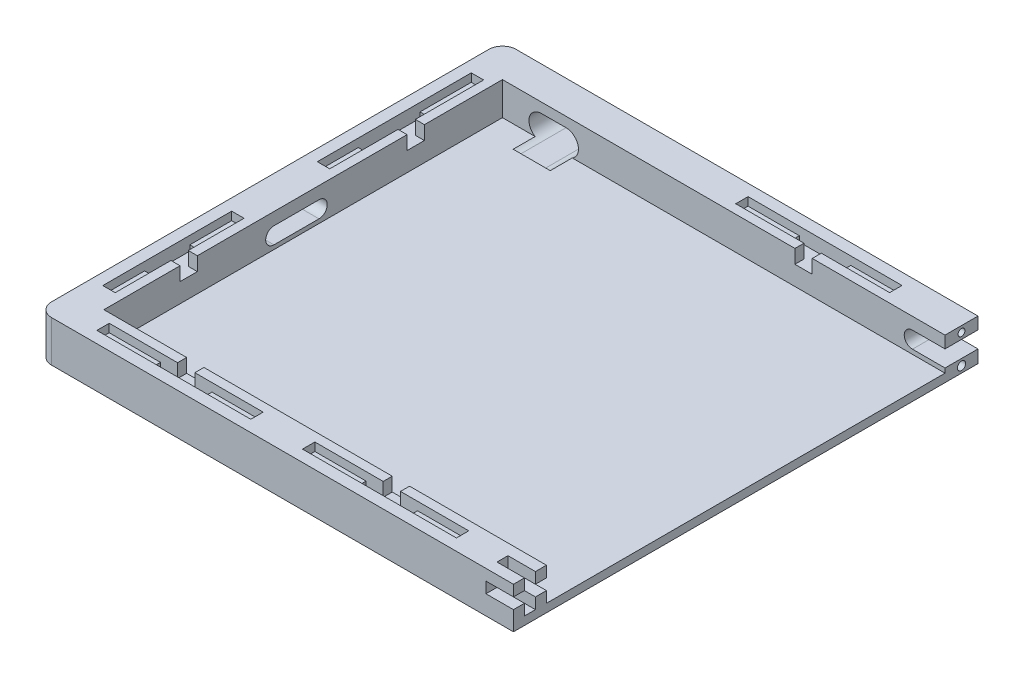
SolidWorks part; units mm, degrees
ref_plane "Front Plane" through (0, 0, 0) normal (0, 0, 1) x (1, 0, 0)
ref_plane "Top Plane" through (0, 0, 0) normal (0, 1, 0) x (1, 0, 0)
ref_plane "Right Plane" through (0, 0, 0) normal (1, 0, 0) x (0, 0, -1)
sketch "Sketch1" plane through (0, 0, 0) normal (0, 1, 0) x (1, 0, 0)
  line L0 (-185.215, 0) -> (43.0487, 0) construction
  line L1 (0, 72.5) -> (-161, 72.5)
  line L2 (0, 215.1028) -> (0, -153.2812) construction
  line L3 (-161, 72.5) -> (-161, -72.5)
  line L4 (-161, -72.5) -> (0, -72.5)
  line L5 (0, 72.5) -> (0, -72.5)
  point P9 (0, 0)
  dimension "D1" = 161
  dimension "D2" = 72.5
extrude "Boss-Extrude1" add sketch "Sketch1" along normal blind 3
sketch "Sketch2" plane through (0, 0, 0) normal (0, 1, 0) x (1, 0, 0)
  line L0 (-224.2217, 0) -> (91.1792, 0) construction
  line L1 (0, 149.3369) -> (0, -151.0656) construction
  line L2 (0, 72.5) -> (0, 84.5)
  line L3 (0, 84.5) -> (-173, 84.5)
  line L4 (-173, 84.5) -> (-173, -84.5)
  line L5 (-173, -84.5) -> (0, -84.5)
  line L6 (0, -84.5) -> (0, -72.5)
  line L8 (-161, 72.5) -> (-161, -72.5) construction
  line L13 (0, -72.5) -> (0, 72.5)
  line L14 (0, 72.5) -> (-161, 72.5)
  line L15 (-161, 72.5) -> (-161, -72.5)
  line L16 (-161, -72.5) -> (0, -72.5)
  line L18 (0, 72.5) -> (-161, 72.5)
  line L19 (-161, 72.5) -> (-161, -72.5)
  line L20 (-161, -72.5) -> (0, -72.5)
  dimension "D1" = 12
  dimension "D2" = 12
  dimension "D3" = 12
  dimension "D4" = 0
extrude "Boss-Extrude2" add sketch "Sketch2" along normal blind 15
sketch "Sketch3" plane through (0, 15, 0) normal (0, 1, 0) x (1, 0, 0)
  line L0 (-161, 72.5) -> (-161, 44.1) construction
  line L1 (-161, -72.5) -> (-161, 72.5) construction
  line L2 (-161, -72.5) -> (-161, -44.8) construction
  line L3 (-161, 44.1) -> (-161, 37.8)
  line L4 (-161, 44.1) -> (-164.3, 44.1)
  line L5 (-161, 37.8) -> (-164.3, 37.8)
  line L6 (-164.3, 44.1) -> (-164.3, 68.95)
  line L7 (-164.3, 37.8) -> (-164.3, 12.95)
  line L8 (-164.3, 68.95) -> (-168.8, 68.95)
  line L9 (-168.8, 68.95) -> (-168.8, 12.95)
  line L10 (-168.8, 12.95) -> (-164.3, 12.95)
  line L11 (-161, 72.5) -> (-161, -72.5) construction
  line L12 (-24.95, -75.8) -> (-49.8, -75.8)
  line L13 (-161, -38.5) -> (-161, -44.8)
  line L14 (-161, -38.5) -> (-164.3, -38.5)
  line L15 (-161, -44.8) -> (-164.3, -44.8)
  line L16 (-164.3, -38.5) -> (-164.3, -18.2)
  line L17 (-164.3, -18.2) -> (-168.8, -18.2)
  line L18 (-168.8, -18.2) -> (-168.8, -65.1)
  line L19 (-168.8, -65.1) -> (-164.3, -65.1)
  line L20 (-164.3, -65.1) -> (-164.3, -44.8)
  line L21 (-24.95, -80.3) -> (-24.95, -75.8)
  line L22 (-80.95, -80.3) -> (-24.95, -80.3)
  line L23 (-80.95, -75.8) -> (-80.95, -80.3)
  line L24 (-56.1, -75.8) -> (-80.95, -75.8)
  line L25 (-56.1, -72.5) -> (-56.1, -75.8)
  line L26 (-49.8, -72.5) -> (-56.1, -72.5)
  line L27 (-49.8, -75.8) -> (-49.8, -72.5)
  line L28 (-99.75, -80.3) -> (-99.75, -75.8)
  line L29 (-155.75, -80.3) -> (-99.75, -80.3)
  line L30 (-155.75, -75.8) -> (-155.75, -80.3)
  line L31 (-130.9, -75.8) -> (-155.75, -75.8)
  line L32 (-130.9, -72.5) -> (-130.9, -75.8)
  line L33 (-124.6, -72.5) -> (-130.9, -72.5)
  line L34 (-124.6, -75.8) -> (-124.6, -72.5)
  line L35 (-99.75, -75.8) -> (-124.6, -75.8)
  line L36 (0, -72.5) -> (-161, -72.5) construction
  line L37 (-161, -72.5) -> (0, -72.5) construction
  line L38 (-48.3, 75.8) -> (-48.3, 72.5)
  line L39 (-23.45, 75.8) -> (-48.3, 75.8)
  line L40 (-23.45, 80.3) -> (-23.45, 75.8)
  line L41 (-79.45, 80.3) -> (-23.45, 80.3)
  line L42 (-79.45, 75.8) -> (-79.45, 80.3)
  line L43 (-54.6, 75.8) -> (-79.45, 75.8)
  line L44 (-54.6, 72.5) -> (-54.6, 75.8)
  line L45 (-48.3, 72.5) -> (-54.6, 72.5)
  line L46 (-161, 72.5) -> (0, 72.5) construction
  dimension "D1" = 28.4
  dimension "D2" = 56
  dimension "D3" = 6.3
  dimension "D4" = 3.3
  dimension "D5" = 6.3
  dimension "D6" = 20.3
  dimension "D7" = 4.5
  dimension "D8" = 4.5
  dimension "D9" = 27.7
  dimension "D10" = 3.3
  dimension "D11" = 30.1
  dimension "D12" = 6.3
  dimension "D13" = 3.3
  dimension "D14" = 4.5
  dimension "D15" = 56
  dimension "D16" = 68.5
  dimension "D17" = 6.3
  dimension "D18" = 3.3
  dimension "D19" = 4.5
  dimension "D20" = 56
  dimension "D21" = 6.3
  dimension "D22" = 3.3
  dimension "D23" = 4.5
  dimension "D24" = 56
  dimension "D25" = 48.3
extrude "Cut-Extrude1" cut sketch "Sketch3" against normal blind 3
sketch "Sketch4" plane through (0, 12, 0) normal (0, 1, 0) x (1, 0, 0)
  line L1 (-54.6, 72.5) -> (-48.3, 72.5)
  line L2 (-48.3, 72.5) -> (-48.3, 75.8)
  line L3 (-48.3, 75.8) -> (-35.875, 75.8) construction
  line L4 (-130.9, -75.8) -> (-143.325, -75.8) construction
  line L5 (-54.6, 75.8) -> (-67.025, 75.8) construction
  line L6 (-79.45, 75.8) -> (-54.6, 75.8) construction
  line L7 (-48.3, 75.8) -> (-23.45, 75.8) construction
  line L10 (-54.6, 72.5) -> (-54.6, 75.8)
  line L14 (-48.3, 75.8) -> (-42.0875, 75.8)
  line L15 (-161, 44.1) -> (-161, 37.8)
  line L16 (-161, 37.8) -> (-164.3, 37.8)
  line L17 (-164.3, 44.1) -> (-164.3, 56.525) construction
  line L18 (-164.3, 44.1) -> (-164.3, 68.95) construction
  line L19 (-164.3, 37.8) -> (-164.3, 25.375) construction
  line L20 (-164.3, 12.95) -> (-164.3, 37.8) construction
  line L21 (-161, 44.1) -> (-164.3, 44.1)
  line L24 (-130.9, -75.8) -> (-155.75, -75.8) construction
  line L26 (-124.6, -75.8) -> (-112.175, -75.8) construction
  line L30 (-164.3, 44.1) -> (-164.3, 50.3125)
  line L31 (-164.3, 50.3125) -> (-168.8, 50.3125)
  line L32 (-168.8, 68.95) -> (-168.8, 12.95) construction
  line L33 (-168.8, 50.3125) -> (-168.8, 27.8502)
  line L34 (-168.8, 68.95) -> (-168.8, 12.95) construction
  line L35 (-168.8, 27.8502) -> (-164.3, 27.8502)
  line L36 (-164.3, 27.8502) -> (-164.3, 37.8)
  line L37 (-164.3, -38.5) -> (-164.3, -28.35) construction
  line L38 (-164.3, -38.5) -> (-164.3, -18.2) construction
  line L39 (-168.8, -33.425) -> (-168.8, -49.875)
  line L40 (-164.3, -65.1) -> (-164.3, -44.8) construction
  line L41 (-164.3, -33.425) -> (-168.8, -33.425)
  line L42 (-168.8, -18.2) -> (-168.8, -65.1) construction
  line L43 (-164.3, -44.8) -> (-164.3, -54.95) construction
  line L44 (-168.8, -49.875) -> (-164.3, -49.875)
  line L45 (-164.3, -49.875) -> (-164.3, -44.8)
  line L46 (-164.3, -44.8) -> (-161, -44.8)
  line L47 (-161, -44.8) -> (-161, -38.5)
  line L48 (-161, -38.5) -> (-164.3, -38.5)
  line L49 (-164.3, -38.5) -> (-164.3, -33.425)
  line L50 (-99.75, -75.8) -> (-124.6, -75.8) construction
  line L51 (-130.9, -72.5) -> (-130.9, -75.8)
  line L52 (-130.9, -75.8) -> (-137.1125, -75.8)
  line L53 (-137.1125, -75.8) -> (-137.1125, -80.3)
  line L54 (-155.75, -80.3) -> (-99.75, -80.3) construction
  line L55 (-137.1125, -80.3) -> (-118.3875, -80.3)
  line L56 (-118.3875, -80.3) -> (-118.3875, -75.8)
  line L59 (-124.6, -72.5) -> (-130.9, -72.5)
  line L60 (-124.6, -72.5) -> (-124.6, -75.8)
  line L61 (-124.6, -75.8) -> (-118.3875, -75.8)
  line L62 (-56.1, -75.8) -> (-68.525, -75.8) construction
  line L63 (-56.1, -75.8) -> (-80.95, -75.8) construction
  line L64 (-49.8, -75.8) -> (-37.375, -75.8) construction
  line L65 (-24.95, -75.8) -> (-49.8, -75.8) construction
  line L66 (-56.1, -75.8) -> (-62.3125, -75.8)
  line L67 (-62.3125, -75.8) -> (-62.3125, -80.3)
  line L68 (-80.95, -80.3) -> (-24.95, -80.3) construction
  line L69 (-62.3125, -80.3) -> (-43.5875, -80.3)
  line L70 (-43.5875, -80.3) -> (-43.5875, -75.8)
  line L71 (-43.5875, -75.8) -> (-49.8, -75.8)
  line L72 (-49.8, -75.8) -> (-49.8, -72.5)
  line L73 (-49.8, -72.5) -> (-56.1, -72.5)
  line L74 (-56.1, -72.5) -> (-56.1, -75.8)
  line L80 (-54.6, 75.8) -> (-60.8125, 75.8)
  line L81 (-60.8125, 75.8) -> (-60.8125, 80.3)
  line L82 (-23.45, 80.3) -> (-79.45, 80.3) construction
  line L83 (-60.8125, 80.3) -> (-42.0875, 80.3)
  line L84 (-23.45, 80.3) -> (-79.45, 80.3) construction
  line L85 (-42.0875, 80.3) -> (-42.0875, 75.8)
extrude "Cut-Extrude2" cut sketch "Sketch4" against normal blind 2
sketch "Sketch5" plane through (-173, 0, 0) normal (-1, 0, 0) x (0, 0, 1)
  line L0 (0, 7.5) -> (32.6582, 7.5) construction
  line L1 (-84.5, 7.5) -> (0, 7.5) construction
  line L2 (-84.5, 15) -> (-84.5, 0) construction
  line L3 (-84.5, 11.8257) -> (-8.75, 11.8257) construction
  line L4 (-5.75, 10.5) -> (10.63, 10.5)
  line L5 (-5.75, 4.5) -> (10.63, 4.5)
  line L8 (-8.75, 4.845) -> (-8.75, 10.155) construction
  arc A0 (-5.75, 4.5) -> (-5.75, 10.5) centre (-5.75, 7.5) cw
  arc A1 (10.63, 10.5) -> (10.63, 4.5) centre (10.63, 7.5) cw
  point P17 (-5.75, 10.5)
  point P21 (-8.75, 7.5)
  dimension "D2" = 3
  dimension "D1" = 16.38
  dimension "D3" = 75.75
extrude "Cut-Extrude3" cut sketch "Sketch5" against normal blind 12
sketch "Sketch7" plane through (0, 0, -84.5) normal (0, 0, -1) x (-1, 0, 0)
  line L0 (60.062, 7.6343) -> (-60.062, 7.6343) construction
  line L1 (0, 0) -> (173, 0) construction
  line L2 (14.8425, 7.6343) -> (14.8425, 12.6467) construction
  line L3 (-4.5375, 10.6343) -> (11.8425, 10.6343)
  line L4 (-4.5375, 4.6343) -> (11.8425, 4.6343)
  line L5 (0, 11.4722) -> (14.8425, 11.4722) construction
  line L6 (0, 15) -> (0, 0) construction
  arc A0 (-4.5375, 4.6343) -> (-4.5375, 10.6343) centre (-4.5375, 7.6343) cw
  arc A1 (11.8425, 10.6343) -> (11.8425, 4.6343) centre (11.8425, 7.6343) cw
  point P3 (0, 7.6343)
  dimension "D3" = 3
  dimension "D1" = 14.8425
  dimension "D2" = 16.38
  dimension "D4" = 7.6343
extrude "Cut-Extrude5" cut sketch "Sketch7" against normal blind 12
sketch "Sketch8" plane through (0, 0, -84.5) normal (0, 0, -1) x (-1, 0, 0)
  line L0 (173, 7.5) -> (143.1877, 7.5) construction
  line L1 (173, 15) -> (173, 0) construction
  line L2 (173, 7.9) -> (146.86, 7.9) construction
  line L3 (146.86, 7.9) -> (137.86, 7.9) construction
  line L4 (0, 15) -> (173, 15) construction
  line L5 (137.86, 11.4) -> (146.86, 11.4)
  line L6 (137.86, 2.4) -> (146.86, 2.4)
  line L7 (164.2575, 6.9) -> (140.1095, 6.9) construction
  line L8 (142.36, 7.9) -> (142.36, 5.9) construction
  line L9 (146.86, 7.9) -> (146.86, 15.4665) construction
  arc A0 (137.86, 2.4) -> (137.86, 11.4) centre (137.86, 6.9) cw
  arc A1 (146.86, 11.4) -> (146.86, 2.4) centre (146.86, 6.9) cw
  point P19 (142.36, 6.9)
  dimension "D5" = 9
  dimension "D1" = 26.14
  dimension "D2" = 9
  dimension "D3" = 7.1
  dimension "D4" = 9
  dimension "D6" = 1
  dimension "2" = 2
extrude "Cut-Extrude6" cut sketch "Sketch8" against normal blind 20
sketch "Sketch9" plane through (-161, 0, 0) normal (1, 0, 0) x (0, 0, -1)
  line L0 (0, 4.5) -> (0, 3) construction
  line L1 (5.75, 4.5) -> (-10.63, 4.5) construction
  line L2 (72.5, 3) -> (-72.5, 3) construction
  line L3 (40.95, 10) -> (40.95, 3) construction
  line L4 (37.8, 10) -> (44.1, 10) construction
sketch "Sketch10" plane through (0, 0, 0) normal (1, 0, 0) x (0, 0, -1)
  line L0 (-72.5, 3) -> (-72.5, 15) construction
  line L1 (-72.5, 15) -> (-84.5, 15) construction
  line L2 (-84.5, 15) -> (-84.5, 3) construction
  line L3 (-84.5, 15) -> (-84.5, 0) construction
  line L4 (-84.5, 3) -> (-72.5, 3) construction
  line L5 (-72.5, 3) -> (-84.5, 15) construction
  line L6 (-84.5, 15) -> (-72.5, 15) construction
  line L7 (-72.5, 15) -> (-84.5, 3) construction
  line L8 (-78.5, 15.3824) -> (-78.5, 3) construction
  line L9 (-84.5, 9) -> (-71.292, 9) construction
  line L10 (-80.5, 15) -> (-76.5, 15)
  line L11 (-72.5, 7) -> (-72.5, 11)
  line L12 (-76.5, 3) -> (-80.5, 3)
  line L13 (-84.5, 7) -> (-84.5, 11)
  line L14 (-80.5, 15) -> (-80.5, 11)
  line L15 (-80.5, 11) -> (-84.5, 11)
  line L16 (-84.5, 7) -> (-80.5, 7)
  line L17 (-80.5, 7) -> (-80.5, 3)
  line L18 (-76.5, 3) -> (-76.5, 7)
  line L19 (-76.5, 7) -> (-72.5, 7)
  line L20 (-72.5, 11) -> (-76.5, 11)
  line L21 (-76.5, 11) -> (-76.5, 15)
  line L22 (-78.5, 9) -> (-78.5, 15) construction
  line L23 (-72.5, 9) -> (-84.5, 9) construction
  point P15 (-78.5, 15)
  point P19 (-72.5, 9)
  point P22 (-78.5, 3)
  point P25 (-84.5, 9)
  dimension "D1" = 4
  dimension "D2" = 4
  dimension "D3" = 4
  dimension "D4" = 4
  dimension "D5" = 0
extrude "Cut-Extrude8" cut sketch "Sketch10" against normal blind 10
fillet "Fillet2" radius 5 1 edges at (-173, 7.5, 84.5)
fillet "Fillet3" radius 5 1 edges at (-173, 7.5, -84.5)
sketch "Sketch11" plane through (0, 0, 0) normal (1, 0, 0) x (0, 0, -1)
  line L0 (72.5, 4.6343) -> (84.5, 4.6343) construction
  line L1 (72.5, 4.6343) -> (72.5, 0) construction
  line L2 (-84.5, 0) -> (84.5, 0) construction
  line L3 (72.5, 0) -> (84.5, 0) construction
  line L4 (84.5, 0) -> (84.5, 4.6343) construction
  line L5 (78.5, 4.6343) -> (78.5, 0) construction
  line L6 (72.5, 2.3172) -> (84.5, 2.3172) construction
  line L7 (72.5, 15) -> (72.5, 10.6343) construction
  line L8 (72.5, 10.6343) -> (84.5, 10.6343) construction
  line L9 (84.5, 10.6343) -> (84.5, 15) construction
  line L10 (84.5, 15) -> (72.5, 15) construction
  line L11 (72.5, 15) -> (78.5, 15) construction
  line L12 (78.5, 15) -> (78.5, 10.6343) construction
  line L13 (78.5, 10.6343) -> (72.5, 10.6343) construction
  line L14 (72.5, 10.6343) -> (72.5, 12.8172) construction
  line L15 (72.5, 12.8172) -> (84.5, 12.8172) construction
  circle A0 centre (78.5, 2.3172) radius 1.5
  circle A1 centre (78.5, 12.8172) radius 1.25
  dimension "D1" = 3
  dimension "D2" = 2.5
extrude "Cut-Extrude9" cut sketch "Sketch11" against normal blind 10
